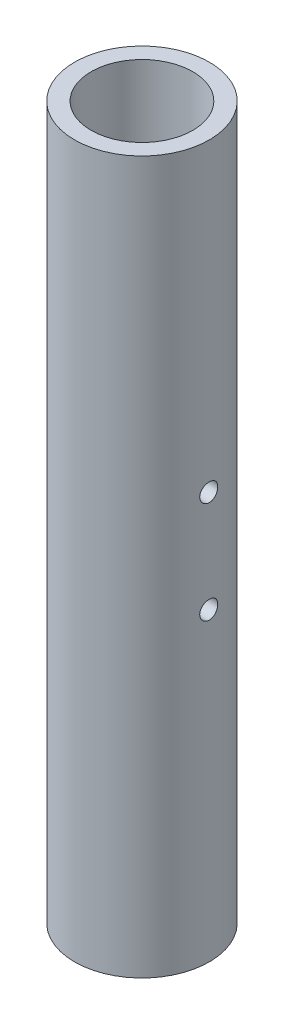
SolidWorks part; units mm, degrees
material "PVC Rigid"
ref_plane "Front Plane" through (0, 0, 0) normal (0, 0, 1) x (1, 0, 0)
ref_plane "Top Plane" through (0, 0, 0) normal (0, 1, 0) x (1, 0, 0)
ref_plane "Right Plane" through (0, 0, 0) normal (1, 0, 0) x (0, 0, -1)
sketch "Sketch1" plane through (0, 0, 0) normal (0, 1, 0) x (1, 0, 0)
  circle A0 centre (0, 0) radius 12.7
  circle A1 centre (0, 0) radius 16.8275
  dimension "D1" = 33.655
  dimension "D2" = 25.4
extrude "Boss-Extrude1" add sketch "Sketch1" along normal blind 177.8
sketch "Sketch2" plane through (0, 0, 0) normal (1, 0, 0) x (0, 0, -1)
  line L0 (0, 0) -> (0, 177.8) construction
  line L1 (16.8275, 177.8) -> (-16.8275, 177.8) construction
  circle A0 centre (0, 76.2) radius 2.2479
  circle A1 centre (0, 101.6) radius 2.2479
  point P9 (0, 88.9)
  dimension "D1" = 4.4958
  dimension "D2" = 25.4
  dimension "D3" = 12.7
extrude "Cut-Extrude1" cut sketch "Sketch2" against normal through all both and the other way through all
